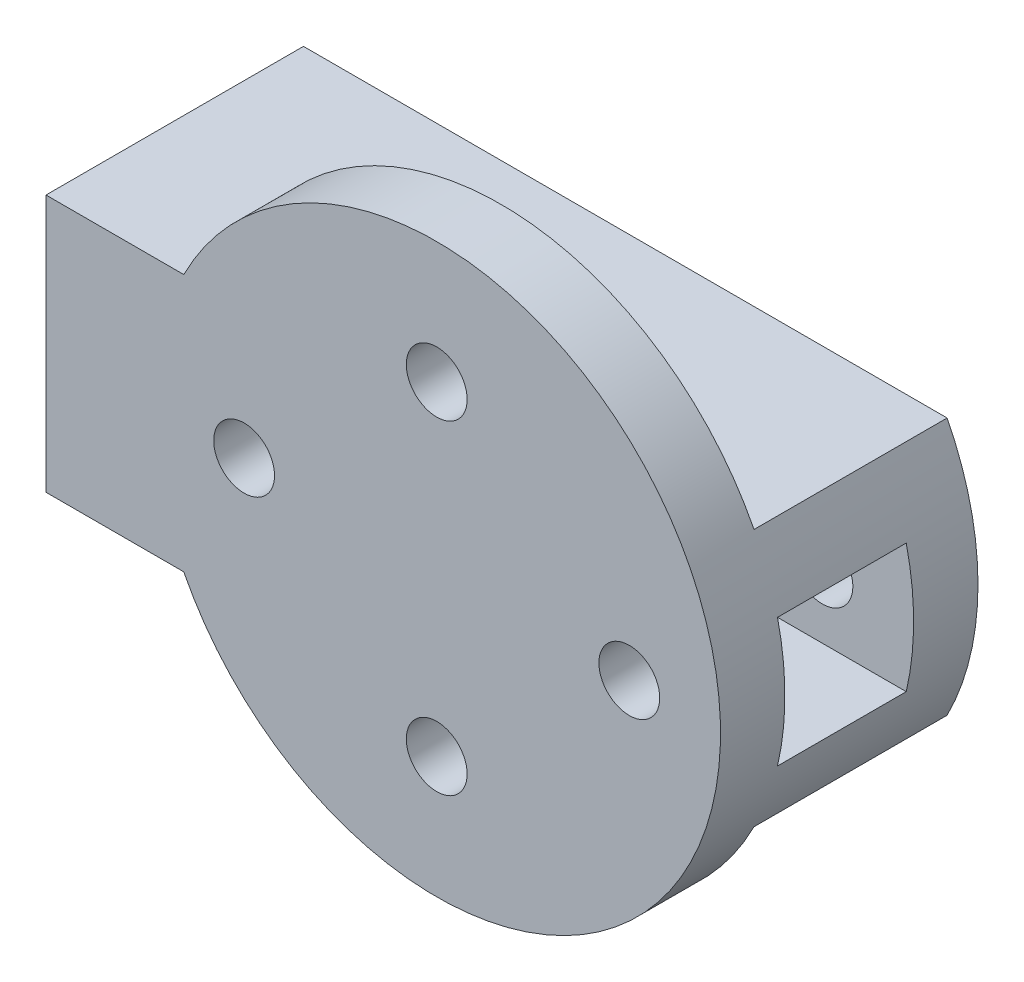
SolidWorks part; units mm, degrees
material "ABS"
ref_plane "Front Plane" through (0, 0, 0) normal (0, 0, 1) x (1, 0, 0)
ref_plane "Top Plane" through (0, 0, 0) normal (0, 1, 0) x (1, 0, 0)
ref_plane "Right Plane" through (0, 0, 0) normal (1, 0, 0) x (0, 0, -1)
sketch "Sketch1" plane through (0, 0, 0) normal (0, 0, 1) x (1, 0, 0)
  circle A0 centre (0, 0) radius 14
  dimension "D1" = 28
extrude "Boss-Extrude1" add sketch "Sketch1" along normal blind 3.175
sketch "Sketch2" plane through (0, 0, 3.175) normal (0, 0, -1) x (-1, 0, 0)
  line L0 (0, 0) -> (-19.1408, 0) construction
  line L1 (-12.4771, 6.35) -> (19.2729, 6.35)
  line L2 (-12.4771, -6.35) -> (19.2729, -6.35)
  line L3 (19.2729, 6.35) -> (19.2729, -6.35)
  circle A0 centre (0, 0) radius 14 construction
  arc A1 (-12.4771, 6.35) -> (-12.4771, -6.35) centre (0, 0) ccw
  dimension "D1" = 31.75
  dimension "D2" = 6.35
extrude "Boss-Extrude2" add sketch "Sketch2" along normal blind 12.7
sketch "Sketch3" plane through (-19.2729, 0, 0) normal (-1, 0, 0) x (0, 0, 1)
  line L0 (-3.175, 6.35) -> (-3.175, -10.2) construction
  line L1 (-9.525, 6.35) -> (3.175, 6.35) construction
  line L2 (0, 0) -> (-18.5331, 0) construction
  line L4 (-6.35, -3.175) -> (0, -3.175)
  line L5 (-6.35, -3.175) -> (-6.35, 3.175)
  line L6 (-6.35, 3.175) -> (0, 3.175)
  line L7 (0, -3.175) -> (0, 3.175)
  line L8 (-6.35, -3.175) -> (0, 3.175) construction
  line L9 (-6.35, 3.175) -> (0, -3.175) construction
  point P7 (-3.175, 0)
  dimension "D1" = 6.35
  dimension "D2" = 6.35
extrude "Cut-Extrude1" cut sketch "Sketch3" against normal through all
sketch "Sketch4" plane through (0, 0, 3.175) normal (0, 0, 1) x (1, 0, 0)
  line L0 (0, 0) -> (0, 20.0244) construction
  line L1 (0, 0) -> (-32.0125, 0) construction
  circle A0 centre (-9.5, 0) radius 1.5
  circle A1 centre (9.5, 0) radius 1.5
  circle A2 centre (0, 8) radius 1.5
  circle A3 centre (0, -8) radius 1.5
  dimension "D1" = 3
  dimension "D2" = 9.5
  dimension "D3" = 3
  dimension "D4" = 8
extrude "Cut-Extrude2" cut sketch "Sketch4" against normal through all
